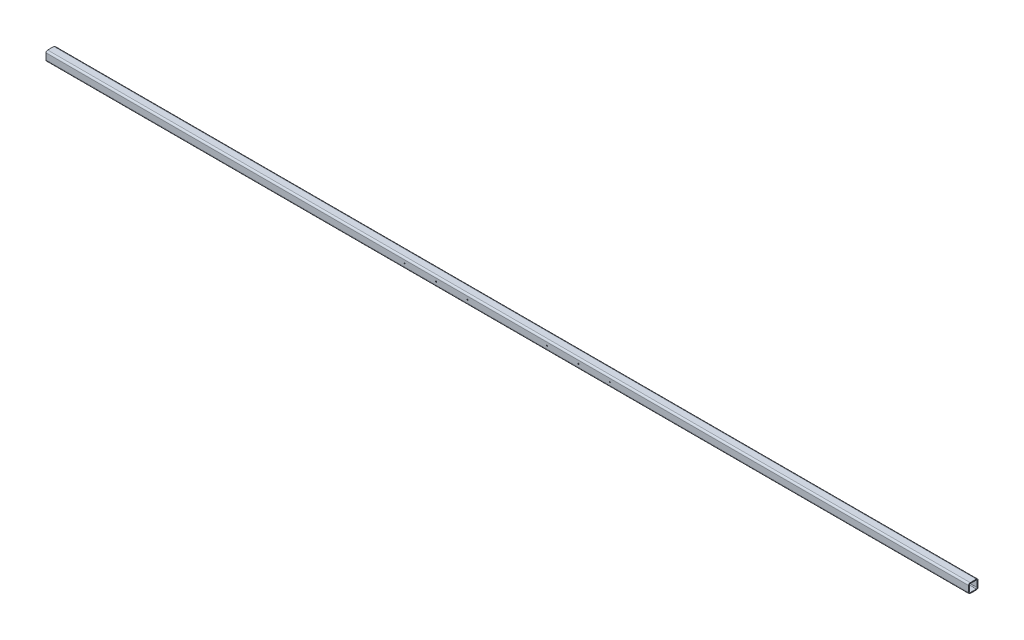
SolidWorks part; units mm, degrees
material "Q235"
ref_plane "前视" through (0, 0, 0) normal (0, 0, 1) x (1, 0, 0)
ref_plane "上视" through (0, 0, 0) normal (0, 1, 0) x (1, 0, 0)
ref_plane "右视" through (0, 0, 0) normal (1, 0, 0) x (0, 0, -1)
sketch "草图1" plane through (0, 0, 0) normal (0, 0, 1) x (1, 0, 0)
  line L0 (0, 0) -> (2932, 0)
  dimension "D1" = 2932
other "结构构件1"
ref_plane "基准面1" through (0, 0, 0) normal (1, 0, 0) x (0, 1, 0)
sketch "Sketch1" plane through (0, 0, 0) normal (1, 0, 0) x (0, 1, 0)
  line L0 (-9.8, -12.4) -> (9.8, -12.4)
  line L1 (-12.4, -9.8) -> (-12.4, 9.8)
  line L2 (9.8, 12.4) -> (-9.8, 12.4)
  line L3 (12.4, 9.8) -> (12.4, -9.8)
  line L4 (-9.8, -15) -> (9.8, -15)
  line L5 (-15, -9.8) -> (-15, 9.8)
  line L6 (9.8, 15) -> (-9.8, 15)
  line L7 (15, 9.8) -> (15, -9.8)
  arc A0 (15, 9.8) -> (9.8, 15) centre (9.8, 9.8) ccw
  arc A1 (9.8, -15) -> (15, -9.8) centre (9.8, -9.8) ccw
  arc A2 (-15, -9.8) -> (-9.8, -15) centre (-9.8, -9.8) ccw
  arc A3 (-9.8, 15) -> (-15, 9.8) centre (-9.8, 9.8) ccw
  arc A4 (-9.8, 12.4) -> (-12.4, 9.8) centre (-9.8, 9.8) ccw
  arc A5 (12.4, 9.8) -> (9.8, 12.4) centre (9.8, 9.8) ccw
  arc A6 (9.8, -12.4) -> (12.4, -9.8) centre (9.8, -9.8) ccw
  arc A7 (-12.4, -9.8) -> (-9.8, -12.4) centre (-9.8, -9.8) ccw
  point P0 (-15, 0)
  point P1 (15, 0)
  point P2 (0, 15)
  point P3 (0, -15)
  point P4 (0, 0)
  point P5 (-15, -15)
  point P6 (15, -15)
  point P7 (15, 15)
  point P8 (-15, 15)
  point P33 (0, 0)
  dimension "D1" = 5.2
  dimension "Thickness" = 2.6
  dimension "V_leg" = 30
hole_wizard "M4 螺纹孔1" positions "草图4" profile "草图3" tap size "M4" standard "Gb"
sketch "草图4" plane through (0, -15, 0) normal (0, -1, 0) x (-1, 0, 0)
  line L0 (0, 0) -> (-2932, 0) construction
  line L1 (0, 0) -> (-1466, 0) construction
  line L2 (-1466, 0) -> (-1466, -15) construction
  line L3 (-2932, -15) -> (0, -15) construction
  point P0 (-20.95, 0)
  point P4 (-50.95, 0)
  point P16 (-2881.05, 0)
  point P17 (-2911.05, 0)
  dimension "D1" = 30
  dimension "D2" = 2830.1
sketch "草图3" plane through (20.95, -15, 0) normal (1, 0, 0) x (0, 0, -1)
  line L0 (0, 0) -> (0, 11.0914)
  line L1 (0, 11.0914) -> (1.65, 10.1)
  line L2 (1.65, 10.1) -> (1.65, 0)
  line L5 (1.65, 0) -> (0, 0)
  line L10 (0, 11.0914) -> (-1.65, 10.1) construction
  line L11 (0, -6.35) -> (0, 107.95) construction
  dimension "螺纹孔钻头直径" = 3.3
  dimension "螺纹孔钻头深度" = 10.1
  dimension "导头角度" = 118
cosmetic thread "孔螺蚊线1" parameters "D1"=2.6, "D2"=4
cosmetic thread "孔螺蚊线2" parameters "D1"=2.6, "D2"=4
cosmetic thread "孔螺蚊线3" parameters "D1"=2.6, "D2"=4
cosmetic thread "孔螺蚊线4" parameters "D1"=2.6, "D2"=4
hole_wizard "M4 螺纹孔2" positions "草图6" profile "草图5" tap size "M4" standard "Gb"
sketch "草图6" plane through (0, 0, 15) normal (0, 0, 1) x (1, 0, 0)
  line L0 (0, 0) -> (1466, 0) construction
  line L1 (0, 0) -> (2932, 0) construction
  line L2 (1466, 0) -> (1466, 15) construction
  line L4 (2932, 15) -> (0, 15) construction
  point P0 (1139.95, 0)
  point P2 (1239.95, 0)
  point P4 (1339.95, 0)
  point P17 (1592.05, 0)
  point P18 (1692.05, 0)
  point P19 (1792.05, 0)
  dimension "D1" = 100
  dimension "D2" = 100
  dimension "D3" = 252.1
sketch "草图5" plane through (1139.95, 0, 15) normal (1, 0, 0) x (0, -1, 0)
  line L0 (0, 0) -> (0, 11.0914)
  line L1 (0, 11.0914) -> (1.65, 10.1)
  line L2 (1.65, 10.1) -> (1.65, 0)
  line L5 (1.65, 0) -> (0, 0)
  line L10 (0, 11.0914) -> (-1.65, 10.1) construction
  line L11 (0, -6.35) -> (0, 107.95) construction
  dimension "螺纹孔钻头直径" = 3.3
  dimension "螺纹孔钻头深度" = 10.1
  dimension "导头角度" = 118
cosmetic thread "孔螺蚊线5" parameters "D1"=2.6, "D2"=4
cosmetic thread "孔螺蚊线6" parameters "D1"=2.6, "D2"=4
cosmetic thread "孔螺蚊线7" parameters "D1"=2.6, "D2"=4
cosmetic thread "孔螺蚊线8" parameters "D1"=2.6, "D2"=4
cosmetic thread "孔螺蚊线9" parameters "D1"=2.6, "D2"=4
cosmetic thread "孔螺蚊线10" parameters "D1"=2.6, "D2"=4
